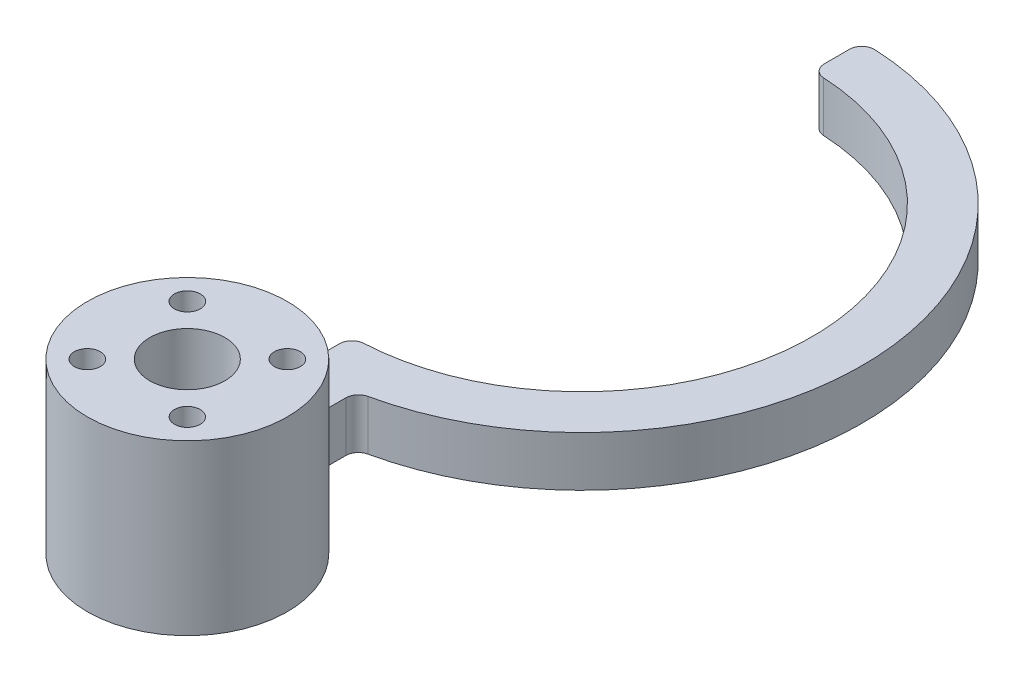
SolidWorks part; units mm, degrees
ref_plane "Front Plane" through (0, 0, 0) normal (0, 0, 1) x (1, 0, 0)
ref_plane "Top Plane" through (0, 0, 0) normal (0, 1, 0) x (1, 0, 0)
ref_plane "Right Plane" through (0, 0, 0) normal (1, 0, 0) x (0, 0, -1)
sketch "Sketch1" plane through (0, 0, 0) normal (0, 1, 0) x (1, 0, 0)
  line L0 (0, 44.83) -> (0, 36.83)
  line L1 (0, -36.83) -> (0, -46.83)
  line L2 (0, -46.83) -> (0, -58.83)
  line L3 (8, -44.1104) -> (8, -56.1104)
  line L8 (16.967, -80.0812) -> (0.967, -80.0812) construction
  line L13 (16.967, -80.0812) -> (16.967, -64.0812) construction
  line L21 (16.967, -64.0812) -> (0.967, -64.0812) construction
  line L22 (0.967, -80.0812) -> (0.967, -64.0812) construction
  line L23 (16.967, -80.0812) -> (0.967, -64.0812) construction
  line L24 (16.967, -64.0812) -> (0.967, -80.0812) construction
  arc A0 (0, -36.83) -> (0, 36.83) centre (0, 0) ccw
  arc A1 (8, -44.1104) -> (0, 44.83) centre (0, 0) ccw
  arc A7 (0, -58.83) -> (23.0776, -79.6236) centre (8.967, -72.0812) ccw
  circle A8 centre (0.967, -64.0812) radius 2.075
  circle A9 centre (16.967, -64.0812) radius 2.075
  circle A10 centre (16.967, -80.0812) radius 2.075
  circle A11 centre (0.967, -80.0812) radius 2.075
  arc A12 (0, -58.83) -> (8, -56.1104) centre (8.967, -72.0812) ccw
  circle A13 centre (8.967, -72.0812) radius 6.0032
  dimension "D1" = 73.66
  dimension "D8" = 4.15
  dimension "D6" = 16
  dimension "D2" = 8
  dimension "D3" = 8
  dimension "D4" = 12
  dimension "D9" = 10
  dimension "D7" = 16
  dimension "D5" = 12
extrude "Boss-Extrude2" add sketch "Sketch1" along normal blind 8 contours A7 A12 L3 A1 L0 A0 L1 L2 A8 A9 A10 A11
fillet "Fillet1" radius 2 6 edges at (0, 4, -36.83) (0, 4, -44.83) (8, 4, 56.1104) (8, 4, 44.1104) (0, 4, 58.83) (0, 4, 36.83)
sketch "Sketch2" plane through (0, 8, 0) normal (0, 1, 0) x (1, 0, 0)
  circle A0 centre (8.967, -72.0812) radius 16
  circle A1 centre (0.967, -64.0812) radius 2.075
  circle A2 centre (8.967, -72.0812) radius 6.0032
  circle A3 centre (16.967, -64.0812) radius 2.075
  circle A4 centre (16.967, -80.0812) radius 2.0591
  circle A5 centre (0.967, -80.0812) radius 2.075
extrude "Boss-Extrude3" add sketch "Sketch2" along normal blind 19
equation "\"innerSmall\"= 2.9in"
equation "\"thick\"= 8mm"
equation "\"D1@Sketch1\"=\"innerSmall\""
equation "\"D2@Sketch1\"=\"thick\""
equation "\"D3@Sketch1\"=\"thick\""
equation "\"D7@Sketch1\"=16mm"
